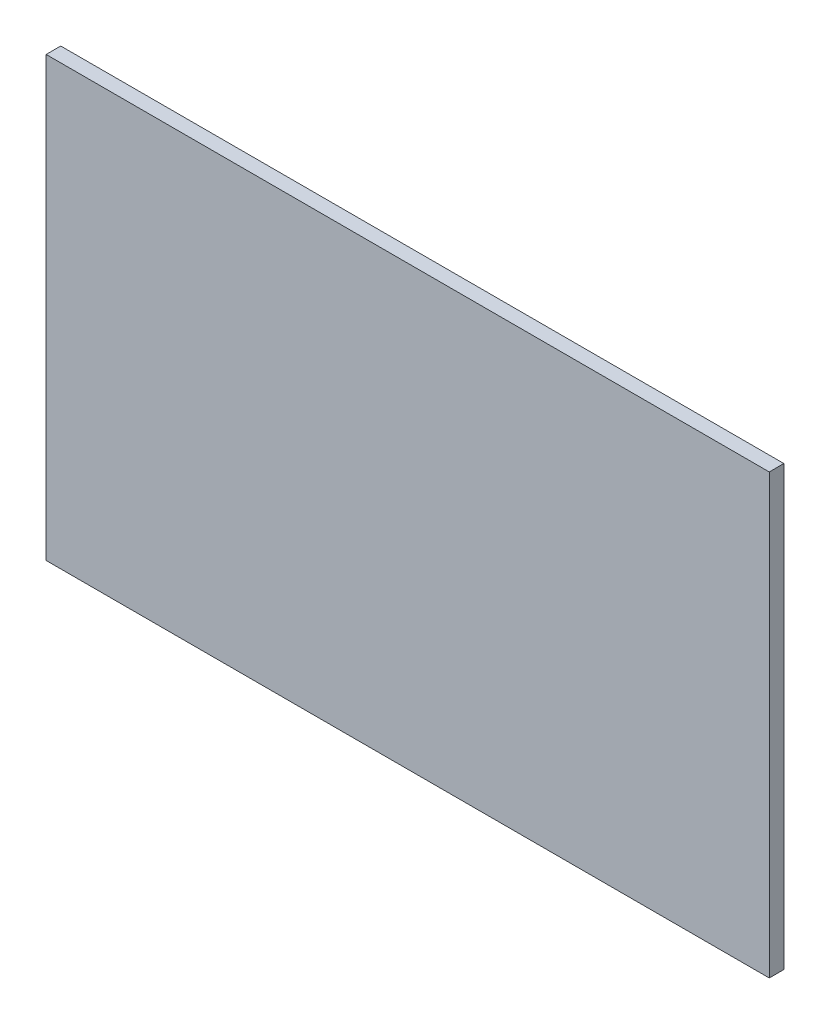
SolidWorks part; units mm, degrees
ref_plane "前视基准面" through (0, 0, 0) normal (0, 0, 1) x (1, 0, 0)
ref_plane "上视基准面" through (0, 0, 0) normal (0, 1, 0) x (1, 0, 0)
ref_plane "右视基准面" through (0, 0, 0) normal (1, 0, 0) x (0, 0, -1)
sketch "草图1" plane through (0, 0, 0) normal (0, 0, 1) x (1, 0, 0)
  line L1 (-80.8623, 23.2993) -> (414.1377, 23.2993)
  line L2 (-80.8623, 23.2993) -> (-80.8623, -476.7007)
  line L3 (-80.8623, -476.7007) -> (414.1377, -476.7007)
  line L4 (414.1377, 23.2993) -> (414.1377, -476.7007)
extrude "凸台-拉伸1" add sketch "草图1" along normal blind 10
sketch "草图2" plane through (0, 0, 10) normal (0, 0, 1) x (1, 0, 0)
  line L0 (414.1377, -476.7007) -> (414.1377, 23.2993) construction
  line L1 (-80.8623, -476.7007) -> (414.1377, -476.7007)
  line L2 (-80.8623, -476.7007) -> (-80.8623, -276.7007)
  line L3 (-80.8623, -276.7007) -> (414.1377, -276.7007)
  line L4 (414.1377, -476.7007) -> (414.1377, -276.7007)
extrude "切除-拉伸1" cut sketch "草图2" against normal blind 10
